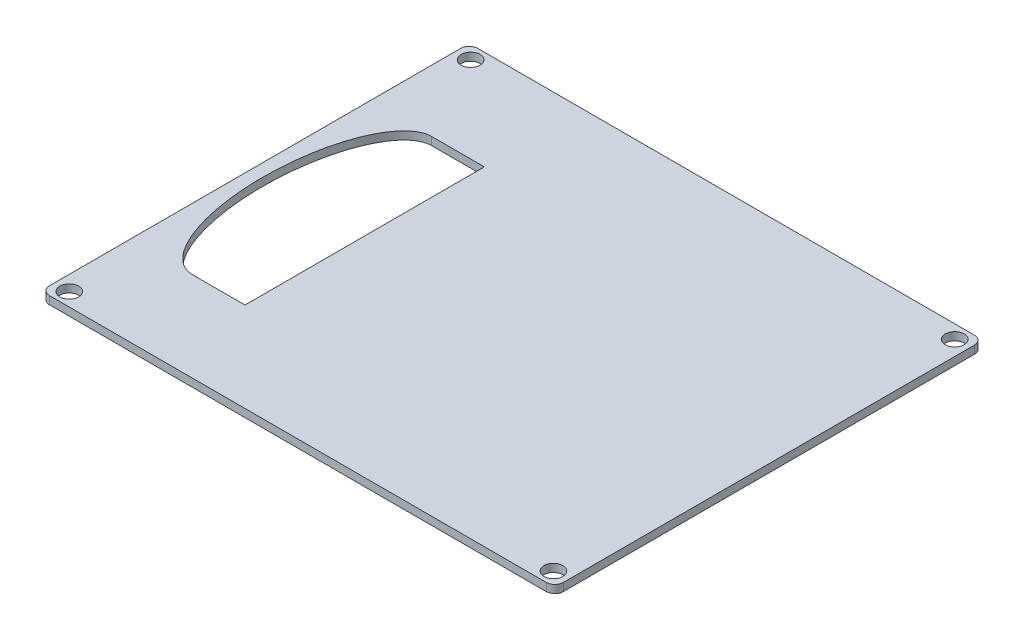
SolidWorks part; units mm, degrees
ref_plane "Front Plane" through (0, 0, 0) normal (0, 0, 1) x (1, 0, 0)
ref_plane "Top Plane" through (0, 0, 0) normal (0, 1, 0) x (1, 0, 0)
ref_plane "Right Plane" through (0, 0, 0) normal (1, 0, 0) x (0, 0, -1)
sketch "Sketch1" plane through (0, 0, 0) normal (0, 1, 0) x (1, 0, 0)
  line L1 (-76.2, 63.5) -> (76.2, 63.5)
  line L2 (-76.2, 63.5) -> (-76.2, -63.5)
  line L3 (-76.2, -63.5) -> (76.2, -63.5)
  line L4 (76.2, 63.5) -> (76.2, -63.5)
  line L5 (-76.2, 63.5) -> (76.2, -63.5) construction
  line L6 (-76.2, -63.5) -> (76.2, 63.5) construction
  point P0 (0, 0)
  dimension "D1" = 152.4
  dimension "D2" = 127
extrude "Boss-Extrude1" add sketch "Sketch1" along normal blind 2.3622
sketch "Sketch2" plane through (0, 2.3622, 0) normal (0, 1, 0) x (1, 0, 0)
  circle A0 centre (71.7948, -59.5104) radius 2.794
  circle A1 centre (71.7948, 59.5104) radius 2.794
  dimension "D1" = 5.588
  dimension "D2" = 5.588
extrude "Cut-Extrude1" cut sketch "Sketch2" against normal through all
sketch "Sketch3" plane through (0, 0, 63.5) normal (0, 0, 1) x (1, 0, 0)
  line L0 (0, 2.3622) -> (0, -1.818) construction
  line L1 (-76.2, 2.3622) -> (76.2, 2.3622) construction
  line L2 (0, 2.3622) -> (0, 0) construction
ref_plane "Plane1" through (0, 0, 0) normal (1, 0, 0) x (0, -1, 0)
mirror "Mirror1" about plane through (0, 0, 0) normal (1, 0, 0) of "Cut-Extrude1"
fillet "Fillet1" radius 2.54 4 edges at (-76.2, 1.1811, 63.5) (76.2, 1.1811, 63.5) (76.2, 1.1811, -63.5) (-76.2, 1.1811, -63.5)
sketch "Sketch4" plane through (0, 2.3622, 0) normal (0, 1, 0) x (1, 0, 0)
  line L1 (-57.8579, 34.0444) -> (-42.2579, 34.0444)
  line L2 (-57.8579, 34.0444) -> (-57.8579, -36.9245)
  line L3 (-57.8579, -36.9245) -> (-42.2579, -36.9245)
  line L4 (-42.2579, 34.0444) -> (-42.2579, -36.9245)
extrude "Cut-Extrude2" cut sketch "Sketch4" against normal through all
sketch "Sketch5" plane through (0, 2.3622, 0) normal (0, 1, 0) x (1, 0, 0)
  line L0 (-57.8579, 34.0444) -> (-57.8579, -36.9245) construction
  ellipse E0 centre (-57.8579, -1.4401) end of major axis (-57.8579, -36.9245) minor radius 14.605
  dimension "D1" = 29.21
extrude "Cut-Extrude3" cut sketch "Sketch5" against normal through all
